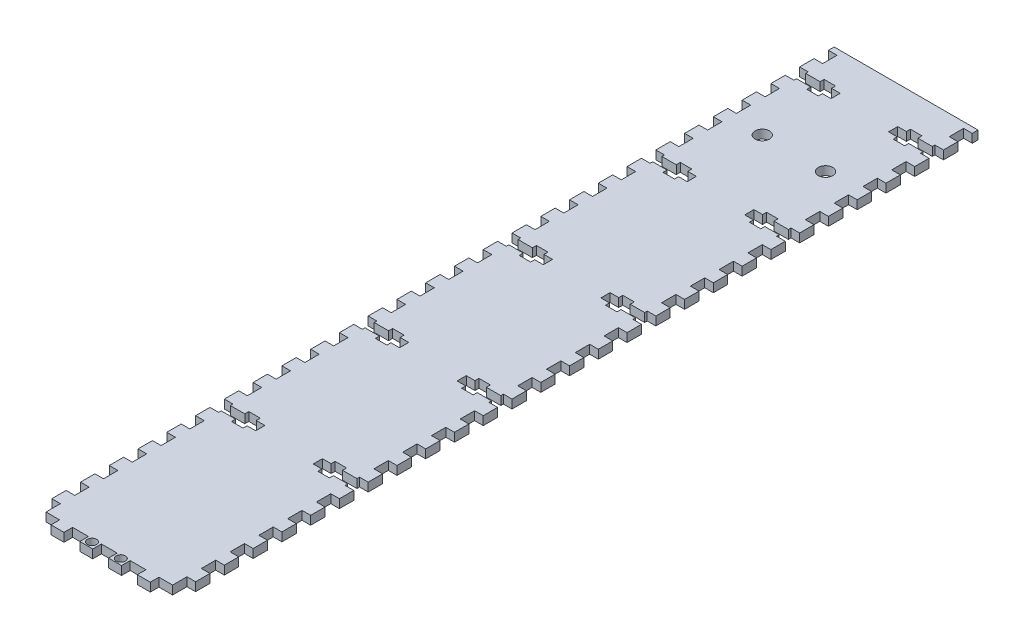
SolidWorks part; units mm, degrees
ref_plane "Plan de face" through (0, 0, 0) normal (0, 0, 1) x (1, 0, 0)
ref_plane "Plan de dessus" through (0, 0, 0) normal (0, 1, 0) x (1, 0, 0)
ref_plane "Plan de droite" through (0, 0, 0) normal (1, 0, 0) x (0, 0, -1)
sketch "Sketch1" plane through (0, 0, 0) normal (0, 0, 1) x (1, 0, 0)
  line L1 (-79.7436, 30.1282) -> (-29.7436, 30.1282)
  line L2 (-79.7436, 30.1282) -> (-79.7436, 27.1282)
  line L3 (-79.7436, 27.1282) -> (-29.7436, 27.1282)
  line L4 (-29.7436, 30.1282) -> (-29.7436, 27.1282)
  dimension "D1" = 50
  dimension "D2" = 3
extrude "Boss-Extrude1" add sketch "Sketch1" along normal blind 277
sketch "Sketch3" plane through (0, 30.1282, 0) normal (0, 1, 0) x (1, 0, 0)
  line L0 (-79.7436, -277) -> (-76.7436, -277)
  line L1 (-29.7436, -277) -> (-79.7436, -277) construction
  line L2 (-29.7436, 0) -> (-79.7436, 0) construction
  line L3 (-54.7436, 0) -> (-54.7436, -277) construction
  line L4 (-29.7436, -277) -> (-32.7436, -277)
  line L5 (-29.7436, -277) -> (-29.7436, -272)
  line L6 (-29.7436, -272) -> (-32.7436, -272)
  line L7 (-32.7436, -277) -> (-32.7436, -272)
  line L8 (-79.7436, -277) -> (-79.7436, -272)
  line L9 (-79.7436, -272) -> (-76.7436, -272)
  line L10 (-76.7436, -277) -> (-76.7436, -272)
  line L11 (-79.7436, -267) -> (-76.7436, -267)
  line L12 (-76.7436, -267) -> (-76.7436, -262)
  line L13 (-79.7436, -262) -> (-76.7436, -262)
  line L14 (-79.7436, -267) -> (-79.7436, -262)
  line L15 (-29.7436, -267) -> (-29.7436, -262)
  line L16 (-29.7436, -267) -> (-32.7436, -267)
  line L17 (-32.7436, -267) -> (-32.7436, -262)
  line L18 (-29.7436, -262) -> (-32.7436, -262)
  line L19 (-79.7436, -257) -> (-76.7436, -257)
  line L20 (-76.7436, -257) -> (-76.7436, -252)
  line L21 (-79.7436, -252) -> (-76.7436, -252)
  line L22 (-79.7436, -257) -> (-79.7436, -252)
  line L23 (-29.7436, -257) -> (-29.7436, -252)
  line L24 (-29.7436, -257) -> (-32.7436, -257)
  line L25 (-32.7436, -257) -> (-32.7436, -252)
  line L26 (-29.7436, -252) -> (-32.7436, -252)
  line L27 (-79.7436, -247) -> (-76.7436, -247)
  line L28 (-76.7436, -247) -> (-76.7436, -242)
  line L29 (-79.7436, -242) -> (-76.7436, -242)
  line L30 (-79.7436, -247) -> (-79.7436, -242)
  line L31 (-29.7436, -247) -> (-29.7436, -242)
  line L32 (-29.7436, -247) -> (-32.7436, -247)
  line L33 (-32.7436, -247) -> (-32.7436, -242)
  line L34 (-29.7436, -242) -> (-32.7436, -242)
  line L35 (-79.7436, -237) -> (-76.7436, -237)
  line L36 (-76.7436, -237) -> (-76.7436, -232)
  line L37 (-79.7436, -232) -> (-76.7436, -232)
  line L38 (-79.7436, -237) -> (-79.7436, -232)
  line L39 (-29.7436, -237) -> (-29.7436, -232)
  line L40 (-29.7436, -237) -> (-32.7436, -237)
  line L41 (-32.7436, -237) -> (-32.7436, -232)
  line L42 (-29.7436, -232) -> (-32.7436, -232)
  line L43 (-79.7436, -227) -> (-76.7436, -227)
  line L44 (-76.7436, -227) -> (-76.7436, -222)
  line L45 (-79.7436, -222) -> (-76.7436, -222)
  line L46 (-79.7436, -227) -> (-79.7436, -222)
  line L47 (-29.7436, -227) -> (-29.7436, -222)
  line L48 (-29.7436, -227) -> (-32.7436, -227)
  line L49 (-32.7436, -227) -> (-32.7436, -222)
  line L50 (-29.7436, -222) -> (-32.7436, -222)
  line L51 (-79.7436, -217) -> (-76.7436, -217)
  line L52 (-76.7436, -217) -> (-76.7436, -212)
  line L53 (-79.7436, -212) -> (-76.7436, -212)
  line L54 (-79.7436, -217) -> (-79.7436, -212)
  line L55 (-29.7436, -217) -> (-29.7436, -212)
  line L56 (-29.7436, -217) -> (-32.7436, -217)
  line L57 (-32.7436, -217) -> (-32.7436, -212)
  line L58 (-29.7436, -212) -> (-32.7436, -212)
  line L59 (-79.7436, -207) -> (-76.7436, -207)
  line L60 (-76.7436, -207) -> (-76.7436, -202)
  line L61 (-79.7436, -202) -> (-76.7436, -202)
  line L62 (-79.7436, -207) -> (-79.7436, -202)
  line L63 (-29.7436, -207) -> (-29.7436, -202)
  line L64 (-29.7436, -207) -> (-32.7436, -207)
  line L65 (-32.7436, -207) -> (-32.7436, -202)
  line L66 (-29.7436, -202) -> (-32.7436, -202)
  line L67 (-79.7436, -197) -> (-76.7436, -197)
  line L68 (-76.7436, -197) -> (-76.7436, -192)
  line L69 (-79.7436, -192) -> (-76.7436, -192)
  line L70 (-79.7436, -197) -> (-79.7436, -192)
  line L71 (-29.7436, -197) -> (-29.7436, -192)
  line L72 (-29.7436, -197) -> (-32.7436, -197)
  line L73 (-32.7436, -197) -> (-32.7436, -192)
  line L74 (-29.7436, -192) -> (-32.7436, -192)
  line L75 (-79.7436, -187) -> (-76.7436, -187)
  line L76 (-76.7436, -187) -> (-76.7436, -182)
  line L77 (-79.7436, -182) -> (-76.7436, -182)
  line L78 (-79.7436, -187) -> (-79.7436, -182)
  line L79 (-29.7436, -187) -> (-29.7436, -182)
  line L80 (-29.7436, -187) -> (-32.7436, -187)
  line L81 (-32.7436, -187) -> (-32.7436, -182)
  line L82 (-29.7436, -182) -> (-32.7436, -182)
  line L83 (-79.7436, -177) -> (-76.7436, -177)
  line L84 (-76.7436, -177) -> (-76.7436, -172)
  line L85 (-79.7436, -172) -> (-76.7436, -172)
  line L86 (-79.7436, -177) -> (-79.7436, -172)
  line L87 (-29.7436, -177) -> (-29.7436, -172)
  line L88 (-29.7436, -177) -> (-32.7436, -177)
  line L89 (-32.7436, -177) -> (-32.7436, -172)
  line L90 (-29.7436, -172) -> (-32.7436, -172)
  line L91 (-79.7436, -167) -> (-76.7436, -167)
  line L92 (-76.7436, -167) -> (-76.7436, -162)
  line L93 (-79.7436, -162) -> (-76.7436, -162)
  line L94 (-79.7436, -167) -> (-79.7436, -162)
  line L95 (-29.7436, -167) -> (-29.7436, -162)
  line L96 (-29.7436, -167) -> (-32.7436, -167)
  line L97 (-32.7436, -167) -> (-32.7436, -162)
  line L98 (-29.7436, -162) -> (-32.7436, -162)
  line L99 (-79.7436, -157) -> (-76.7436, -157)
  line L100 (-76.7436, -157) -> (-76.7436, -152)
  line L101 (-79.7436, -152) -> (-76.7436, -152)
  line L102 (-79.7436, -157) -> (-79.7436, -152)
  line L103 (-29.7436, -157) -> (-29.7436, -152)
  line L104 (-29.7436, -157) -> (-32.7436, -157)
  line L105 (-32.7436, -157) -> (-32.7436, -152)
  line L106 (-29.7436, -152) -> (-32.7436, -152)
  line L107 (-79.7436, -147) -> (-76.7436, -147)
  line L108 (-76.7436, -147) -> (-76.7436, -142)
  line L109 (-79.7436, -142) -> (-76.7436, -142)
  line L110 (-79.7436, -147) -> (-79.7436, -142)
  line L111 (-29.7436, -147) -> (-29.7436, -142)
  line L112 (-29.7436, -147) -> (-32.7436, -147)
  line L113 (-32.7436, -147) -> (-32.7436, -142)
  line L114 (-29.7436, -142) -> (-32.7436, -142)
  line L115 (-79.7436, -137) -> (-76.7436, -137)
  line L116 (-76.7436, -137) -> (-76.7436, -132)
  line L117 (-79.7436, -132) -> (-76.7436, -132)
  line L118 (-79.7436, -137) -> (-79.7436, -132)
  line L119 (-29.7436, -137) -> (-29.7436, -132)
  line L120 (-29.7436, -137) -> (-32.7436, -137)
  line L121 (-32.7436, -137) -> (-32.7436, -132)
  line L122 (-29.7436, -132) -> (-32.7436, -132)
  line L123 (-79.7436, -127) -> (-76.7436, -127)
  line L124 (-76.7436, -127) -> (-76.7436, -122)
  line L125 (-79.7436, -122) -> (-76.7436, -122)
  line L126 (-79.7436, -127) -> (-79.7436, -122)
  line L127 (-29.7436, -127) -> (-29.7436, -122)
  line L128 (-29.7436, -127) -> (-32.7436, -127)
  line L129 (-32.7436, -127) -> (-32.7436, -122)
  line L130 (-29.7436, -122) -> (-32.7436, -122)
  line L131 (-79.7436, -117) -> (-76.7436, -117)
  line L132 (-76.7436, -117) -> (-76.7436, -112)
  line L133 (-79.7436, -112) -> (-76.7436, -112)
  line L134 (-79.7436, -117) -> (-79.7436, -112)
  line L135 (-29.7436, -117) -> (-29.7436, -112)
  line L136 (-29.7436, -117) -> (-32.7436, -117)
  line L137 (-32.7436, -117) -> (-32.7436, -112)
  line L138 (-29.7436, -112) -> (-32.7436, -112)
  line L139 (-79.7436, -107) -> (-76.7436, -107)
  line L140 (-76.7436, -107) -> (-76.7436, -102)
  line L141 (-79.7436, -102) -> (-76.7436, -102)
  line L142 (-79.7436, -107) -> (-79.7436, -102)
  line L143 (-29.7436, -107) -> (-29.7436, -102)
  line L144 (-29.7436, -107) -> (-32.7436, -107)
  line L145 (-32.7436, -107) -> (-32.7436, -102)
  line L146 (-29.7436, -102) -> (-32.7436, -102)
  line L147 (-79.7436, -97) -> (-76.7436, -97)
  line L148 (-76.7436, -97) -> (-76.7436, -92)
  line L149 (-79.7436, -92) -> (-76.7436, -92)
  line L150 (-79.7436, -97) -> (-79.7436, -92)
  line L151 (-29.7436, -97) -> (-29.7436, -92)
  line L152 (-29.7436, -97) -> (-32.7436, -97)
  line L153 (-32.7436, -97) -> (-32.7436, -92)
  line L154 (-29.7436, -92) -> (-32.7436, -92)
  line L155 (-79.7436, -87) -> (-76.7436, -87)
  line L156 (-76.7436, -87) -> (-76.7436, -82)
  line L157 (-79.7436, -82) -> (-76.7436, -82)
  line L158 (-79.7436, -87) -> (-79.7436, -82)
  line L159 (-29.7436, -87) -> (-29.7436, -82)
  line L160 (-29.7436, -87) -> (-32.7436, -87)
  line L161 (-32.7436, -87) -> (-32.7436, -82)
  line L162 (-29.7436, -82) -> (-32.7436, -82)
  line L163 (-79.7436, -77) -> (-76.7436, -77)
  line L164 (-76.7436, -77) -> (-76.7436, -72)
  line L165 (-79.7436, -72) -> (-76.7436, -72)
  line L166 (-79.7436, -77) -> (-79.7436, -72)
  line L167 (-29.7436, -77) -> (-29.7436, -72)
  line L168 (-29.7436, -77) -> (-32.7436, -77)
  line L169 (-32.7436, -77) -> (-32.7436, -72)
  line L170 (-29.7436, -72) -> (-32.7436, -72)
  line L171 (-79.7436, -67) -> (-76.7436, -67)
  line L172 (-76.7436, -67) -> (-76.7436, -62)
  line L173 (-79.7436, -62) -> (-76.7436, -62)
  line L174 (-79.7436, -67) -> (-79.7436, -62)
  line L175 (-29.7436, -67) -> (-29.7436, -62)
  line L176 (-29.7436, -67) -> (-32.7436, -67)
  line L177 (-32.7436, -67) -> (-32.7436, -62)
  line L178 (-29.7436, -62) -> (-32.7436, -62)
  line L179 (-79.7436, -57) -> (-76.7436, -57)
  line L180 (-76.7436, -57) -> (-76.7436, -52)
  line L181 (-79.7436, -52) -> (-76.7436, -52)
  line L182 (-79.7436, -57) -> (-79.7436, -52)
  line L183 (-29.7436, -57) -> (-29.7436, -52)
  line L184 (-29.7436, -57) -> (-32.7436, -57)
  line L185 (-32.7436, -57) -> (-32.7436, -52)
  line L186 (-29.7436, -52) -> (-32.7436, -52)
  line L187 (-79.7436, -47) -> (-76.7436, -47)
  line L188 (-76.7436, -47) -> (-76.7436, -42)
  line L189 (-79.7436, -42) -> (-76.7436, -42)
  line L190 (-79.7436, -47) -> (-79.7436, -42)
  line L191 (-29.7436, -47) -> (-29.7436, -42)
  line L192 (-29.7436, -47) -> (-32.7436, -47)
  line L193 (-32.7436, -47) -> (-32.7436, -42)
  line L194 (-29.7436, -42) -> (-32.7436, -42)
  line L195 (-79.7436, -37) -> (-76.7436, -37)
  line L196 (-76.7436, -37) -> (-76.7436, -32)
  line L197 (-79.7436, -32) -> (-76.7436, -32)
  line L198 (-79.7436, -37) -> (-79.7436, -32)
  line L199 (-29.7436, -37) -> (-29.7436, -32)
  line L200 (-29.7436, -37) -> (-32.7436, -37)
  line L201 (-32.7436, -37) -> (-32.7436, -32)
  line L202 (-29.7436, -32) -> (-32.7436, -32)
  line L203 (-79.7436, -27) -> (-76.7436, -27)
  line L204 (-76.7436, -27) -> (-76.7436, -22)
  line L205 (-79.7436, -22) -> (-76.7436, -22)
  line L206 (-79.7436, -27) -> (-79.7436, -22)
  line L207 (-29.7436, -27) -> (-29.7436, -22)
  line L208 (-29.7436, -27) -> (-32.7436, -27)
  line L209 (-32.7436, -27) -> (-32.7436, -22)
  line L210 (-29.7436, -22) -> (-32.7436, -22)
  line L211 (-79.7436, -17) -> (-76.7436, -17)
  line L212 (-76.7436, -17) -> (-76.7436, -12)
  line L213 (-79.7436, -12) -> (-76.7436, -12)
  line L214 (-79.7436, -17) -> (-79.7436, -12)
  line L215 (-29.7436, -17) -> (-29.7436, -12)
  line L216 (-29.7436, -17) -> (-32.7436, -17)
  line L217 (-32.7436, -17) -> (-32.7436, -12)
  line L218 (-29.7436, -12) -> (-32.7436, -12)
  line L219 (-79.7436, -7) -> (-76.7436, -7)
  line L220 (-76.7436, -7) -> (-76.7436, -2)
  line L221 (-79.7436, -2) -> (-76.7436, -2)
  line L222 (-79.7436, -7) -> (-79.7436, -2)
  line L223 (-29.7436, -7) -> (-29.7436, -2)
  line L224 (-29.7436, -7) -> (-32.7436, -7)
  line L225 (-32.7436, -7) -> (-32.7436, -2)
  line L226 (-29.7436, -2) -> (-32.7436, -2)
  dimension "D1" = 3
  dimension "D2" = 5
  dimension "D3" = 28
extrude "Cut-Extrude1" cut sketch "Sketch3" against normal blind 3
sketch "Sketch6" plane through (0, 0, 277) normal (0, 0, 1) x (1, 0, 0)
  line L0 (-32.7436, 30.1282) -> (-76.7436, 30.1282) construction
  line L1 (-71.9936, 30.1282) -> (-67.4936, 30.1282)
  line L2 (-71.9936, 30.1282) -> (-71.9936, 27.1282)
  line L3 (-71.9936, 27.1282) -> (-67.4936, 27.1282)
  line L4 (-67.4936, 30.1282) -> (-67.4936, 27.1282)
  line L5 (-76.7436, 27.1282) -> (-32.7436, 27.1282) construction
  line L6 (-76.7436, 27.1282) -> (-76.7436, 30.1282) construction
  line L7 (-61.9936, 30.1282) -> (-61.9936, 27.1282)
  line L8 (-61.9936, 30.1282) -> (-57.4936, 30.1282)
  line L9 (-57.4936, 30.1282) -> (-57.4936, 27.1282)
  line L10 (-61.9936, 27.1282) -> (-57.4936, 27.1282)
  line L11 (-51.9936, 30.1282) -> (-51.9936, 27.1282)
  line L12 (-51.9936, 30.1282) -> (-47.4936, 30.1282)
  line L13 (-47.4936, 30.1282) -> (-47.4936, 27.1282)
  line L14 (-51.9936, 27.1282) -> (-47.4936, 27.1282)
  line L15 (-41.9936, 30.1282) -> (-41.9936, 27.1282)
  line L16 (-41.9936, 30.1282) -> (-37.4936, 30.1282)
  line L17 (-37.4936, 30.1282) -> (-37.4936, 27.1282)
  line L18 (-41.9936, 27.1282) -> (-37.4936, 27.1282)
  line L20 (-32.7436, 27.1282) -> (-32.7436, 30.1282) construction
  dimension "D1" = 4.75
  dimension "D2" = 4.5
  dimension "D4" = 4.75
  dimension "D3" = 4
extrude "Boss-Extrude2" add sketch "Sketch6" along normal blind 3
sketch "Sketch9" plane through (-32.7436, 0, 0) normal (1, 0, 0) x (0, 0, -1)
  line L0 (-267, 27.1282) -> (-262, 30.1282) construction
  line L1 (-262, 27.1282) -> (-267, 27.1282) construction
  line L2 (-262.9, 30.1282) -> (-266.1, 30.1282)
  line L3 (-262.9, 30.1282) -> (-262.9, 27.1282)
  line L4 (-262.9, 27.1282) -> (-266.1, 27.1282)
  line L5 (-266.1, 30.1282) -> (-266.1, 27.1282)
  line L6 (-262.9, 30.1282) -> (-266.1, 27.1282) construction
  line L7 (-262.9, 27.1282) -> (-266.1, 30.1282) construction
  line L8 (-212.9, 30.1282) -> (-212.9, 27.1282)
  line L9 (-212.9, 30.1282) -> (-216.1, 30.1282)
  line L10 (-216.1, 30.1282) -> (-216.1, 27.1282)
  line L11 (-212.9, 27.1282) -> (-216.1, 27.1282)
  line L12 (-162.9, 30.1282) -> (-162.9, 27.1282)
  line L13 (-162.9, 30.1282) -> (-166.1, 30.1282)
  line L14 (-166.1, 30.1282) -> (-166.1, 27.1282)
  line L15 (-162.9, 27.1282) -> (-166.1, 27.1282)
  line L16 (-112.9, 30.1282) -> (-112.9, 27.1282)
  line L17 (-112.9, 30.1282) -> (-116.1, 30.1282)
  line L18 (-116.1, 30.1282) -> (-116.1, 27.1282)
  line L19 (-112.9, 27.1282) -> (-116.1, 27.1282)
  line L20 (-62.9, 30.1282) -> (-62.9, 27.1282)
  line L21 (-62.9, 30.1282) -> (-66.1, 30.1282)
  line L22 (-66.1, 30.1282) -> (-66.1, 27.1282)
  line L23 (-62.9, 27.1282) -> (-66.1, 27.1282)
  line L24 (-12.9, 30.1282) -> (-12.9, 27.1282)
  line L25 (-12.9, 30.1282) -> (-16.1, 30.1282)
  line L26 (-16.1, 30.1282) -> (-16.1, 27.1282)
  line L27 (-12.9, 27.1282) -> (-16.1, 27.1282)
  point P4 (-264.5, 28.6282)
  dimension "D1" = 3.2
  dimension "D2" = 6
extrude "Cut-Extrude2" cut sketch "Sketch9" against normal blind 12
sketch "Sketch10" plane through (-76.7436, 0, 0) normal (-1, 0, 0) x (0, 0, 1)
  line L0 (267, 30.1282) -> (262, 27.1282) construction
  line L1 (267, 30.1282) -> (262, 30.1282) construction
  line L2 (262.9, 27.1282) -> (266.1, 27.1282)
  line L3 (262.9, 27.1282) -> (262.9, 30.1282)
  line L4 (262.9, 30.1282) -> (266.1, 30.1282)
  line L5 (266.1, 27.1282) -> (266.1, 30.1282)
  line L6 (262.9, 27.1282) -> (266.1, 30.1282) construction
  line L7 (262.9, 30.1282) -> (266.1, 27.1282) construction
  line L8 (212.9, 27.1282) -> (212.9, 30.1282)
  line L9 (212.9, 27.1282) -> (216.1, 27.1282)
  line L10 (216.1, 27.1282) -> (216.1, 30.1282)
  line L11 (212.9, 30.1282) -> (216.1, 30.1282)
  line L12 (162.9, 27.1282) -> (162.9, 30.1282)
  line L13 (162.9, 27.1282) -> (166.1, 27.1282)
  line L14 (166.1, 27.1282) -> (166.1, 30.1282)
  line L15 (162.9, 30.1282) -> (166.1, 30.1282)
  line L16 (112.9, 27.1282) -> (112.9, 30.1282)
  line L17 (112.9, 27.1282) -> (116.1, 27.1282)
  line L18 (116.1, 27.1282) -> (116.1, 30.1282)
  line L19 (112.9, 30.1282) -> (116.1, 30.1282)
  line L20 (62.9, 27.1282) -> (62.9, 30.1282)
  line L21 (62.9, 27.1282) -> (66.1, 27.1282)
  line L22 (66.1, 27.1282) -> (66.1, 30.1282)
  line L23 (62.9, 30.1282) -> (66.1, 30.1282)
  line L24 (12.9, 27.1282) -> (12.9, 30.1282)
  line L25 (12.9, 27.1282) -> (16.1, 27.1282)
  line L26 (16.1, 27.1282) -> (16.1, 30.1282)
  line L27 (12.9, 30.1282) -> (16.1, 30.1282)
  point P4 (264.5, 28.6282)
  dimension "D1" = 3.2
  dimension "D2" = 6
extrude "Cut-Extrude3" cut sketch "Sketch10" against normal blind 12
sketch "Sketch11" plane through (0, 27.1282, 0) normal (0, -1, 0) x (1, 0, 0)
  line L0 (-54.7436, 277) -> (-54.7436, 0) construction
  line L1 (-71.7436, 267.5) -> (-67.7436, 267.5)
  line L2 (-71.7436, 267.5) -> (-71.7436, 261.5)
  line L3 (-71.7436, 261.5) -> (-67.7436, 261.5)
  line L4 (-67.7436, 267.5) -> (-67.7436, 261.5)
  line L5 (-57.4936, 277) -> (-51.9936, 277) construction
  line L6 (-79.7436, 0) -> (-29.7436, 0) construction
  line L8 (-76.7436, 267) -> (-76.7436, 266.1) construction
  line L9 (-37.7436, 261.5) -> (-41.7436, 261.5)
  line L10 (-41.7436, 267.5) -> (-41.7436, 261.5)
  line L11 (-37.7436, 267.5) -> (-41.7436, 267.5)
  line L12 (-37.7436, 267.5) -> (-37.7436, 261.5)
  line L13 (-71.7436, 217.5) -> (-71.7436, 211.5)
  line L14 (-71.7436, 217.5) -> (-67.7436, 217.5)
  line L15 (-67.7436, 217.5) -> (-67.7436, 211.5)
  line L16 (-71.7436, 211.5) -> (-67.7436, 211.5)
  line L17 (-37.7436, 211.5) -> (-41.7436, 211.5)
  line L18 (-41.7436, 217.5) -> (-41.7436, 211.5)
  line L19 (-37.7436, 217.5) -> (-41.7436, 217.5)
  line L20 (-37.7436, 217.5) -> (-37.7436, 211.5)
  line L21 (-71.7436, 167.5) -> (-71.7436, 161.5)
  line L22 (-71.7436, 167.5) -> (-67.7436, 167.5)
  line L23 (-67.7436, 167.5) -> (-67.7436, 161.5)
  line L24 (-71.7436, 161.5) -> (-67.7436, 161.5)
  line L25 (-37.7436, 161.5) -> (-41.7436, 161.5)
  line L26 (-41.7436, 167.5) -> (-41.7436, 161.5)
  line L27 (-37.7436, 167.5) -> (-41.7436, 167.5)
  line L28 (-37.7436, 167.5) -> (-37.7436, 161.5)
  line L29 (-71.7436, 117.5) -> (-71.7436, 111.5)
  line L30 (-71.7436, 117.5) -> (-67.7436, 117.5)
  line L31 (-67.7436, 117.5) -> (-67.7436, 111.5)
  line L32 (-71.7436, 111.5) -> (-67.7436, 111.5)
  line L33 (-37.7436, 111.5) -> (-41.7436, 111.5)
  line L34 (-41.7436, 117.5) -> (-41.7436, 111.5)
  line L35 (-37.7436, 117.5) -> (-41.7436, 117.5)
  line L36 (-37.7436, 117.5) -> (-37.7436, 111.5)
  line L37 (-71.7436, 67.5) -> (-71.7436, 61.5)
  line L38 (-71.7436, 67.5) -> (-67.7436, 67.5)
  line L39 (-67.7436, 67.5) -> (-67.7436, 61.5)
  line L40 (-71.7436, 61.5) -> (-67.7436, 61.5)
  line L41 (-37.7436, 61.5) -> (-41.7436, 61.5)
  line L42 (-41.7436, 67.5) -> (-41.7436, 61.5)
  line L43 (-37.7436, 67.5) -> (-41.7436, 67.5)
  line L44 (-37.7436, 67.5) -> (-37.7436, 61.5)
  line L45 (-71.7436, 17.5) -> (-71.7436, 11.5)
  line L46 (-71.7436, 17.5) -> (-67.7436, 17.5)
  line L47 (-67.7436, 17.5) -> (-67.7436, 11.5)
  line L48 (-71.7436, 11.5) -> (-67.7436, 11.5)
  line L49 (-37.7436, 11.5) -> (-41.7436, 11.5)
  line L50 (-41.7436, 17.5) -> (-41.7436, 11.5)
  line L51 (-37.7436, 17.5) -> (-41.7436, 17.5)
  line L52 (-37.7436, 17.5) -> (-37.7436, 11.5)
  line L53 (-64.7436, 266.1) -> (-64.7436, 262.9) construction
  point P18 (-64.7436, 264.5)
  point P52 (-67.7436, 264.5)
  dimension "D1" = 6
  dimension "D3" = 5
  dimension "D4" = 4
  dimension "D5" = 6
extrude "Cut-Extrude4" cut sketch "Sketch11" against normal blind 12
sketch "Sketch12" plane through (0, 27.1282, 0) normal (0, -1, 0) x (1, 0, 0)
  line L0 (-61.9936, 280) -> (-57.4936, 280) construction
  line L1 (-51.9936, 280) -> (-47.4936, 280) construction
  circle A0 centre (-59.7436, 278) radius 1.6
  circle A1 centre (-49.7436, 278) radius 1.6
  dimension "D1" = 3.2
  dimension "D3" = 3.2
  dimension "D2" = 2
  dimension "D4" = 2
extrude "Cut-Extrude5" cut sketch "Sketch12" against normal blind 12
sketch "Sketch13" plane through (0, 27.1282, 0) normal (0, -1, 0) x (1, 0, 0)
  line L1 (-76.7436, 268.9635) -> (-63.8443, 268.9635)
  line L2 (-76.7436, 268.9635) -> (-76.7436, 257.8916)
  line L3 (-76.7436, 257.8916) -> (-63.8443, 257.8916)
  line L4 (-63.8443, 268.9635) -> (-63.8443, 257.8916)
  line L5 (-45.3248, 270.0119) -> (-32.7436, 270.0119)
  line L6 (-45.3248, 270.0119) -> (-45.3248, 259.0227)
  line L7 (-45.3248, 259.0227) -> (-32.7436, 259.0227)
  line L8 (-32.7436, 270.0119) -> (-32.7436, 259.0227)
  point P11 (-63.022, 257.8916)
  point P12 (-63.8443, 268.9635)
  point P13 (-45.5489, 259.0227)
  point P14 (0, 0)
  point P15 (-45.3248, 270.0119)
extrude "Boss-Extrude3" add sketch "Sketch13" against normal blind 3
sketch "Sketch15" plane through (0, 27.1282, 0) normal (0, -1, 0) x (1, 0, 0)
  line L0 (-54.7436, 0) -> (-54.7436, 54.5316) construction
  line L1 (-79.7436, 0) -> (-29.7436, 0) construction
  circle A0 centre (-65.7436, 39) radius 2.5
  circle A1 centre (-43.7436, 39) radius 2.5
  point P10 (-54.7436, 0)
  dimension "D1" = 5
  dimension "D2" = 11
  dimension "D3" = 39
extrude "Cut-Extrude8" cut sketch "Sketch15" against normal through all
